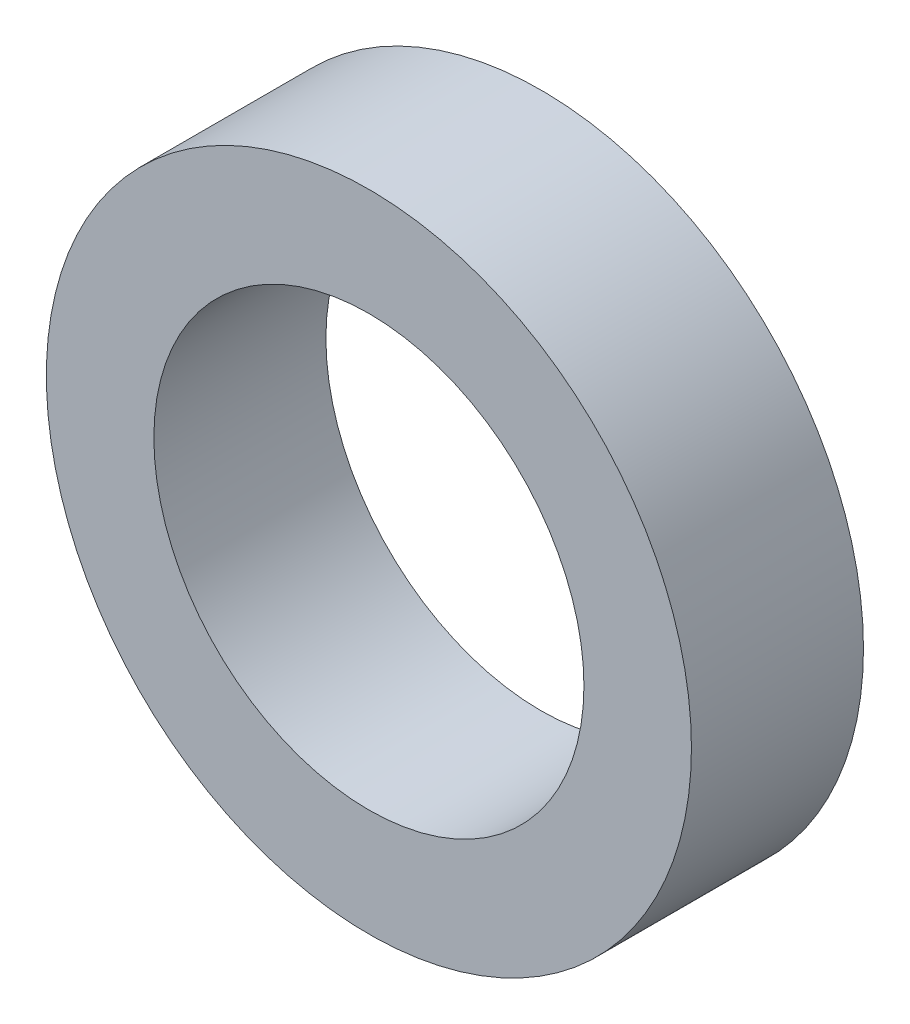
SolidWorks part; units mm, degrees
ref_plane "Plan de face" through (0, 0, 0) normal (0, 0, 1) x (1, 0, 0)
ref_plane "Plan de dessus" through (0, 0, 0) normal (0, 1, 0) x (1, 0, 0)
ref_plane "Plan de droite" through (0, 0, 0) normal (1, 0, 0) x (0, 0, -1)
sketch "Esquisse1" plane through (0, 0, 0) normal (1, 0, 0) x (0, 0, -1)
  line L0 (-12.9348, 0) -> (8.4783, 0) construction
  line L1 (-2, 7.5) -> (2, 7.5)
  line L2 (-2, 7.5) -> (-2, 5)
  line L3 (-2, 5) -> (2, 5)
  line L4 (2, 7.5) -> (2, 5)
  line L5 (-2, 7.5) -> (2, 5) construction
  line L6 (-2, 5) -> (2, 7.5) construction
  point P0 (0, 6.25)
  point P8 (0, 5)
  dimension "D1" = 4
  dimension "D2" = 5
  dimension "D3" = 7.5
revolve "Révolution1" add sketch "Esquisse1" angle 360 about L0
